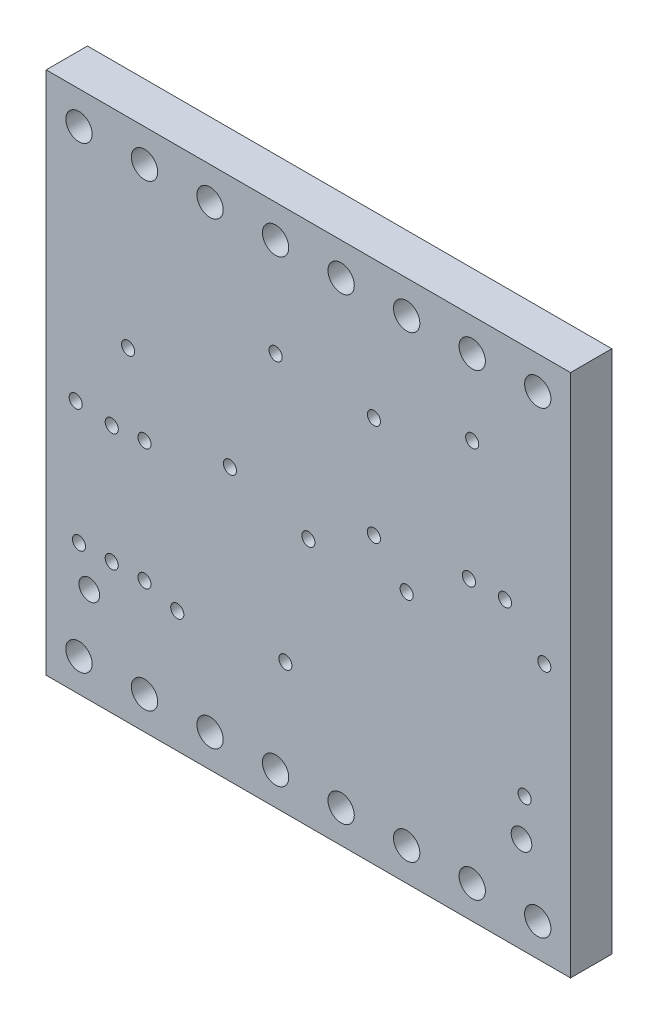
SolidWorks part; units mm, degrees
ref_plane "Front Plane" through (0, 0, 0) normal (0, 0, 1) x (1, 0, 0)
ref_plane "Top Plane" through (0, 0, 0) normal (0, 1, 0) x (1, 0, 0)
ref_plane "Right Plane" through (0, 0, 0) normal (1, 0, 0) x (0, 0, -1)
ref_plane "Dielectric_Layer Layer 1" through (0, 0, 1.6) normal (0, 0, 1) x (1, 0, 0)
sketch "Sketch1" plane through (0, 0, 0) normal (0, 0, 1) x (1, 0, 0)
  line L0 (-10.16, -10.16) -> (-10.16, 10.16)
  line L1 (-10.16, 10.16) -> (10.16, 10.16)
  line L2 (10.16, 10.16) -> (10.16, -10.16)
  line L3 (10.16, -10.16) -> (-10.16, -10.16)
extrude "Board_Outline" add sketch "Sketch1" along normal blind 1.6 separate body
sketch "Sketch2" plane through (0, 0, 0) normal (0, 0, 1) x (1, 0, 0)
  circle A0 centre (8.26, -6.448) radius 0.4
  circle A1 centre (-8.49, -6.448) radius 0.4
  circle A2 centre (-6.985, 2.413) radius 0.254
  circle A3 centre (-3.04, 0.389) radius 0.254
  circle A4 centre (-6.35, -0.381) radius 0.254
  circle A5 centre (-7.62, -5.08) radius 0.254
  circle A6 centre (-7.62, -0.508) radius 0.254
  circle A7 centre (-8.89, -5.08) radius 0.254
  circle A8 centre (0, -0.508) radius 0.254
  circle A9 centre (2.54, 4.826) radius 0.254
  circle A10 centre (2.54, 0.889) radius 0.254
  circle A11 centre (-1.27, 5.08) radius 0.254
  circle A12 centre (-5.08, -5.461) radius 0.254
  circle A13 centre (8.382, -4.953) radius 0.254
  circle A14 centre (-9.017, -0.381) radius 0.254
  circle A15 centre (9.144, -0.127) radius 0.254
  circle A16 centre (3.81, -0.381) radius 0.254
  circle A17 centre (-6.35, -5.08) radius 0.254
  circle A18 centre (7.62, 1.27) radius 0.254
  circle A19 centre (6.223, 1.27) radius 0.254
  circle A20 centre (6.35, 5.969) radius 0.254
  circle A21 centre (-0.889, -5.08) radius 0.254
extrude "NPTH" cut sketch "Sketch2" along normal through all
sketch "Sketch3" plane through (0, 0, 0) normal (0, 0, 1) x (1, 0, 0)
  circle A0 centre (8.89, 8.89) radius 0.51
  circle A1 centre (6.35, 8.89) radius 0.51
  circle A2 centre (3.81, 8.89) radius 0.51
  circle A3 centre (1.27, 8.89) radius 0.51
  circle A4 centre (-1.27, 8.89) radius 0.51
  circle A5 centre (-3.81, 8.89) radius 0.51
  circle A6 centre (-6.35, 8.89) radius 0.51
  circle A7 centre (-8.89, 8.89) radius 0.51
  circle A8 centre (-8.89, -8.89) radius 0.51
  circle A9 centre (-6.35, -8.89) radius 0.51
  circle A10 centre (-3.81, -8.89) radius 0.51
  circle A11 centre (-1.27, -8.89) radius 0.51
  circle A12 centre (1.27, -8.89) radius 0.51
  circle A13 centre (3.81, -8.89) radius 0.51
  circle A14 centre (6.35, -8.89) radius 0.51
  circle A15 centre (8.89, -8.89) radius 0.51
extrude "PTH" cut sketch "Sketch3" along normal through all
